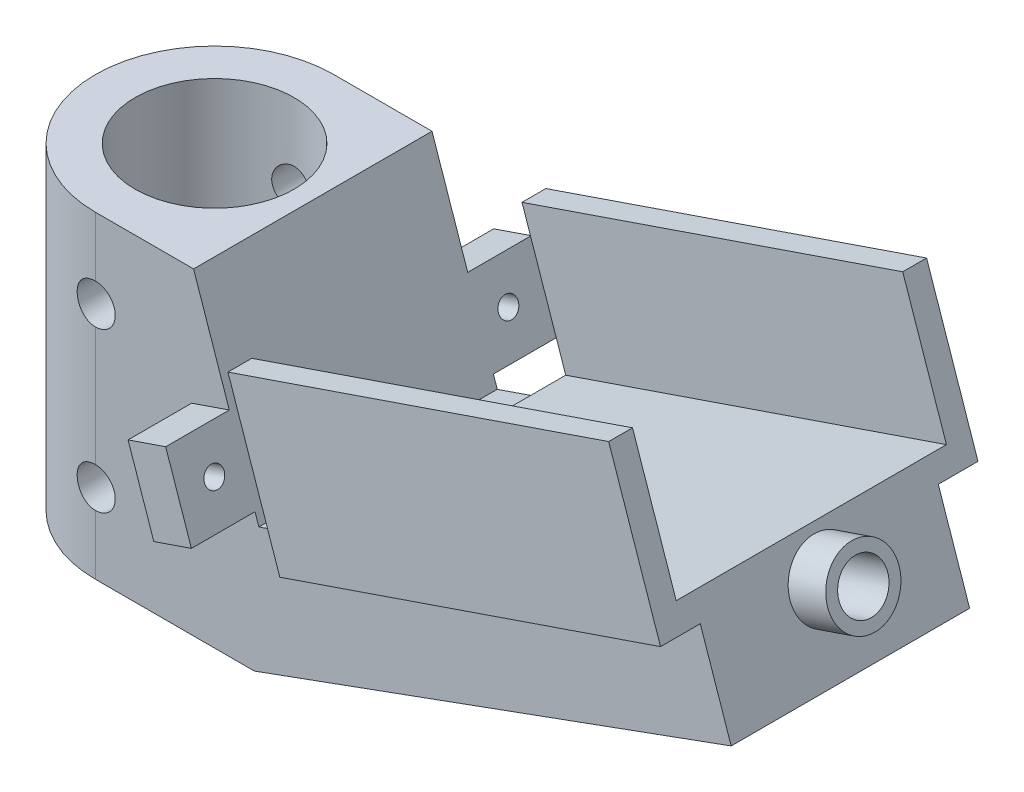
SolidWorks part; units mm, degrees
ref_plane "Plan de face" through (0, 0, 0) normal (0, 0, 1) x (1, 0, 0)
ref_plane "Plan de dessus" through (0, 0, 0) normal (0, 1, 0) x (1, 0, 0)
ref_plane "Plan de droite" through (0, 0, 0) normal (1, 0, 0) x (0, 0, -1)
sketch "Esquisse1" plane through (0, 0, 0) normal (0, 1, 0) x (1, 0, 0)
  line L0 (0, -15) -> (80, -15)
  line L1 (80, -15) -> (80, 15)
  line L2 (80, 15) -> (0, 15)
  circle A0 centre (0, 0) radius 10
  arc A1 (0, 15) -> (0, -15) centre (0, 0) ccw
  dimension "D1" = 20
  dimension "D2" = 15
  dimension "D3" = 80
extrude "Boss.-Extru.1" add sketch "Esquisse1" along normal blind 40
sketch "Esquisse3" plane through (0, 0, 15) normal (0, 0, 1) x (1, 0, 0)
  line L0 (20, 0) -> (80, 0)
  line L1 (0, 0) -> (80, 0) construction
  line L2 (80, 0) -> (80, 21.8382)
  line L3 (80, 40) -> (80, 0) construction
  line L4 (80, 21.8382) -> (20, 0)
  dimension "D1" = 20
  dimension "D2" = 21.8382
extrude "Enlèv. mat.-Extru.1" cut sketch "Esquisse3" against normal through all
sketch "Esquisse4" plane through (0, 0, 15) normal (0, 0, 1) x (1, 0, 0)
  line L0 (80, 21.8382) -> (80, 40)
  line L1 (80, 40) -> (73.7889, 40)
  line L2 (0, 40) -> (80, 40) construction
  line L3 (73.7889, 40) -> (80, 21.8382)
  dimension "D1" = 6.2111
extrude "Enlèv. mat.-Extru.2" cut sketch "Esquisse4" against normal through all
sketch "Esquisse5" plane through (78.3097, 26.7809, 0) normal (0.9462, 0.3236, 0) x (0, 0, -1)
  line L0 (-15, 13.9708) -> (15, -5.2237) construction
  line L1 (15, 13.9708) -> (-15, -5.2237) construction
  circle A0 centre (0, 4.3735) radius 3.075
  dimension "D1" = 6.15
extrude "Enlèv. mat.-Extru.3" cut sketch "Esquisse5" against normal blind 50
sketch "Esquisse6" plane through (0, 0, 15) normal (0, 0, 1) x (1, 0, 0)
  line L0 (75.0833, 36.2152) -> (20.0833, 17.4059)
  line L1 (73.7889, 40) -> (80, 21.8382) construction
  line L2 (20.0833, 17.4059) -> (12.3564, 40)
  line L3 (0, 40) -> (73.7889, 40) construction
  line L4 (12.3564, 40) -> (73.7889, 40)
  line L5 (73.7889, 40) -> (75.0833, 36.2152)
  dimension "D1" = 55
  dimension "D2" = 4
extrude "Enlèv. mat.-Extru.4" cut sketch "Esquisse6" against normal through all
hole_wizard "Trou taraudé M31" positions "Esquisse9" profile "Esquisse10" tap size "M3" standard "ISO"
sketch "Esquisse9" plane through (2.3396, -6.4279, 0) normal (0.342, -0.9397, 0) x (-0.9397, -0.342, 0)
  point P0 (-46.8853, 0)
  point P2 (-70.0894, 0)
sketch "Esquisse10" plane through (46.3973, 9.6078, 0) normal (0, 0, 1) x (0.9397, 0.342, 0)
  line L0 (0, 0) -> (0, 7.2226)
  line L1 (0, 7.2226) -> (1.25, 7.2226)
  line L2 (1.25, 7.2226) -> (1.25, 0)
  line L5 (1.25, 0) -> (0, 0)
  line L11 (0, -6.35) -> (0, 107.95) construction
  dimension "Diamètre du trou pour taraudage jusqu'au prochain" = 2.5
  dimension "Profondeur du trou pour taraudage jusqu'au prochain" = 7.2226
cosmetic thread "Filetage de perçage5" parameters "D2"=3
cosmetic thread "Filetage de perçage6" parameters "D2"=3
sketch "Esquisse11" plane through (0, 0, 15) normal (0, 0, 1) x (1, 0, 0)
  line L0 (20.0833, 17.4059) -> (16.8474, 26.8679)
  line L1 (12.3564, 40) -> (20.0833, 17.4059) construction
  line L2 (16.8474, 26.8679) -> (12.1164, 25.25)
  line L3 (12.1164, 25.25) -> (15.3523, 15.788)
  line L4 (15.3523, 15.788) -> (20.0833, 17.4059)
  dimension "D1" = 10
  dimension "D2" = 5
extrude "Boss.-Extru.2" add sketch "Esquisse11" along normal blind 8
sketch "Esquisse12" plane through (0, 0, -15) normal (0, 0, -1) x (-1, 0, 0)
  line L0 (-20.0833, 17.4059) -> (-16.8474, 26.8679)
  line L1 (-12.3564, 40) -> (-20.0833, 17.4059) construction
  line L2 (-16.8474, 26.8679) -> (-12.1164, 25.25)
  line L3 (-12.1164, 25.25) -> (-15.3523, 15.788)
  line L4 (-15.3523, 15.788) -> (-20.0833, 17.4059)
  dimension "D1" = 5
  dimension "D2" = 10
extrude "Boss.-Extru.3" add sketch "Esquisse12" along normal blind 8
sketch "Esquisse13" plane through (23.3097, 7.9716, 0) normal (0.9462, 0.3236, 0) x (0, 0, -1)
  line L0 (-15, 19.9708) -> (-23, 9.9708) construction
  line L1 (-23, 19.9708) -> (-15, 9.9708) construction
  line L2 (23, 19.9708) -> (15, 9.9708) construction
  line L3 (23, 9.9708) -> (15, 9.9708) construction
  line L4 (15, 19.9708) -> (23, 9.9708) construction
  line L5 (-19, 14.9708) -> (-19, 9.9708) construction
  line L6 (-23, 9.9708) -> (-15, 9.9708) construction
  line L7 (19, 14.9708) -> (19, 9.9708) construction
sketch "Esquisse19" plane through (-3.2264, 9.4343, 0) normal (-0.3236, 0.9462, 0) x (0.9462, 0.3236, 0)
  line L0 (24.6351, -15) -> (82.7624, -15) construction
  line L1 (24.6351, 15) -> (32.1351, 15)
  line L2 (24.6351, 15) -> (24.6351, -15)
  line L3 (24.6351, -15) -> (32.1351, -15)
  line L4 (32.1351, 15) -> (32.1351, -15)
  dimension "D1" = 7.5
extrude "Enlèv. mat.-Extru.5" cut sketch "Esquisse19" against normal blind 1.5
sketch "Esquisse34" plane through (0, 0, 15) normal (0, 0, 1) x (1, 0, 0)
  line L0 (27.1797, 19.8328) -> (75.0833, 36.2152)
  line L1 (27.1797, 19.8328) -> (28.2057, 16.8328)
  line L2 (75.0833, 36.2152) -> (76.1092, 33.2152)
  line L3 (28.2057, 16.8328) -> (76.1092, 33.2152)
  dimension "D1" = 3
extrude "Boss.-Extru.4" add sketch "Esquisse34" along normal blind 5
sketch "Esquisse35" plane through (0, 0, -15) normal (0, 0, -1) x (-1, 0, 0)
  line L0 (-27.1797, 19.8328) -> (-75.0833, 36.2152)
  line L1 (-27.1797, 19.8328) -> (-28.1505, 16.9942)
  line L2 (-75.0833, 36.2152) -> (-76.054, 33.3766)
  line L3 (-28.1505, 16.9942) -> (-76.054, 33.3766)
  dimension "D1" = 3
extrude "Boss.-Extru.5" add sketch "Esquisse35" along normal blind 5
sketch "Esquisse36" plane through (-3.2264, 9.4343, 0) normal (-0.3236, 0.9462, 0) x (0.9462, 0.3236, 0)
  line L0 (32.1351, -20) -> (82.7624, -20)
  line L1 (32.1351, -20) -> (32.1351, -17)
  line L2 (82.7624, -20) -> (82.7624, -17)
  line L3 (32.1351, -17) -> (82.7624, -17)
  line L4 (32.1351, 20) -> (82.7624, 20)
  line L5 (32.1351, 20) -> (32.1351, 17)
  line L6 (82.7624, 20) -> (82.7624, 17)
  line L7 (32.1351, 17) -> (82.7624, 17)
  dimension "D1" = 3
  dimension "D2" = 3
extrude "Boss.-Extru.6" add sketch "Esquisse36" along normal blind 17
sketch "Esquisse37" plane through (23.3097, 7.9716, 0) normal (0.9462, 0.3236, 0) x (0, 0, -1)
  line L0 (-23, 14.9708) -> (-18.5, 14.9708) construction
  line L1 (-23, 9.9708) -> (-23, 19.9708) construction
  line L2 (23, 14.9708) -> (18.5, 14.9708) construction
  line L3 (23, 19.9708) -> (23, 9.9708) construction
  dimension "D1" = 4.5
  dimension "D2" = 4.5
hole_wizard "Trou taraudé M35" positions "Esquisse38" profile "Esquisse39" tap size "M3" standard "ISO"
sketch "Esquisse38" plane through (23.3097, 7.9716, 0) normal (0.9462, 0.3236, 0) x (0, 0, -1)
  point P0 (-18.5, 14.9708)
  point P3 (18.5, 14.9708)
sketch "Esquisse39" plane through (18.4653, 22.1369, 18.5) normal (0, 0, 1) x (-0.3236, 0.9462, 0)
  line L0 (0, 0) -> (0, 5)
  line L1 (0, 5) -> (1.25, 5)
  line L2 (1.25, 5) -> (1.25, 0)
  line L5 (1.25, 0) -> (0, 0)
  line L11 (0, -6.35) -> (0, 107.95) construction
  dimension "Diamètre du trou pour taraudage jusqu'au prochain" = 2.5
  dimension "Profondeur du trou pour taraudage jusqu'au prochain" = 5
cosmetic thread "Filetage de perçage13" parameters "D2"=3
cosmetic thread "Filetage de perçage14" parameters "D2"=3
sketch "Esquisse40" plane through (78.3097, 26.7809, 0) normal (0.9462, 0.3236, 0) x (0, 0, -1)
  line L0 (-3.075, 4.3735) -> (3.075, 4.3735) construction
  line L1 (3.075, 4.3735) -> (0, 7.4485) construction
  line L2 (0, 7.4485) -> (0, 1.2985) construction
  circle A0 centre (0, 4.3735) radius 3.075 construction
  circle A1 centre (0, 4.3735) radius 4.5
  dimension "D1" = 9
extrude "Boss.-Extru.8" add sketch "Esquisse40" along normal blind 5
sketch "Esquisse41" plane through (83.0407, 28.3988, 0) normal (0.9462, 0.3236, 0) x (0, 0, -1)
  line L0 (0, 8.8735) -> (0, -0.1265) construction
  line L1 (0, -0.1265) -> (-4.5, 4.3735) construction
  line L2 (-4.5, 4.3735) -> (4.5, 4.3735) construction
  circle A0 centre (0, 4.3735) radius 4.5 construction
  circle A1 centre (0, 4.3735) radius 3.075
  dimension "D1" = 6.15
extrude "Enlèv. mat.-Extru.7" cut sketch "Esquisse41" against normal blind 5 contours A1
sketch "Esquisse42" plane through (0, 0, 0) normal (0, 0, 1) x (1, 0, 0)
  line L0 (0, 40) -> (0, 0) construction
  circle A0 centre (0, 30) radius 2.5
  circle A1 centre (0, 10) radius 2.5
  dimension "D1" = 5
  dimension "D2" = 5
  dimension "D3" = 10
  dimension "D4" = 30
extrude "Enlèv. mat.-Extru.8" cut sketch "Esquisse42" against normal through all both and the other way through all
